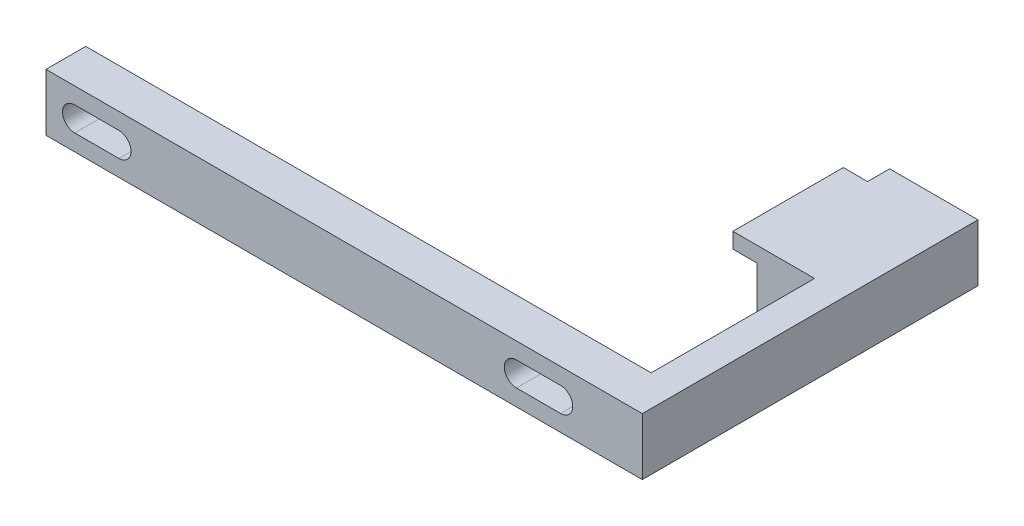
SolidWorks part; units mm, degrees
ref_plane "Front Plane" through (0, 0, 0) normal (0, 0, 1) x (1, 0, 0)
ref_plane "Top Plane" through (0, 0, 0) normal (0, 1, 0) x (1, 0, 0)
ref_plane "Right Plane" through (0, 0, 0) normal (1, 0, 0) x (0, 0, -1)
sketch "Sketch1" plane through (0, 0, 0) normal (0, 0, 1) x (1, 0, 0)
  line L1 (-7.5, -6.4688) -> (127.5, -6.4688)
  line L2 (-7.5, -6.4688) -> (-7.5, 6.4688)
  line L3 (-7.5, 6.4688) -> (127.5, 6.4688)
  line L4 (127.5, -6.4688) -> (127.5, 6.4688)
  point P9 (-7.5, 0)
  dimension "D1" = 12.9376
  dimension "D4" = 135
extrude "Boss-Extrude1" add sketch "Sketch1" along normal blind 9
sketch "Sketch2" plane through (0, 0, 0) normal (0, 0, -1) x (-1, 0, 0)
  line L0 (7.5, -6.4688) -> (-127.5, -6.4688) construction
  line L1 (-127.5, 6.4688) -> (-120.5, 6.4688)
  line L2 (-127.5, 6.4688) -> (-127.5, -6.4688)
  line L3 (-127.5, -6.4688) -> (-120.5, -6.4688)
  line L4 (-120.5, 6.4688) -> (-120.5, -6.4688)
  dimension "D1" = 7
extrude "Boss-Extrude2" add sketch "Sketch2" along direction (0, 0, -1) on the side of the normal offset from surface (54 mm away) 63
sketch "Sketch3" plane through (120.5, 0, 0) normal (-1, 0, 0) x (0, 0, 1)
  line L0 (-54, -6.4688) -> (0, -6.4688) construction
  line L1 (-54, 6.4688) -> (-47, 6.4688)
  line L2 (-54, 6.4688) -> (-54, -6.4688)
  line L3 (-54, -6.4688) -> (-47, -6.4688)
  line L4 (-47, 6.4688) -> (-47, -6.4688)
  dimension "D1" = 7
ref_plane "Plane2" through (97.5, 0, 0) normal (1, 0, 0) x (0, 0, -1)
extrude "Boss-Extrude5" add sketch "Sketch3" along direction (1, 0, 0) on the side of the normal offset from surface (13 mm away) 10 up to plane "Plane2"
sketch "Sketch6" plane through (107.5, 0, 0) normal (-1, 0, 0) x (0, 0, 1)
  line L0 (-37, 6.4688) -> (-37, -6.4688)
  line L1 (-47, 6.4688) -> (0, 6.4688) construction
  line L2 (-47, -6.4688) -> (0, -6.4688) construction
  line L3 (-37, -6.4688) -> (-67, -6.4688)
  line L4 (-67, -6.4688) -> (-67, 6.4688)
  line L5 (-67, 6.4688) -> (-37, 6.4688)
  line L6 (-47, -6.4688) -> (-47, 6.4688) construction
  dimension "D1" = 10
  dimension "D2" = 30
extrude "Boss-Extrude6" add sketch "Sketch6" against normal up to surface (20 mm away) up to face at (127.5, 0, -22.5)
sketch "Sketch7" plane through (107.5, 0, 0) normal (-1, 0, 0) x (0, 0, 1)
  line L3 (-37, -6.4688) -> (-37, 6.4688) construction
  line L5 (-37, -6.4688) -> (-67, -6.4688) construction
  circle A0 centre (-39.75, -3.7188) radius 1.5
  circle A1 centre (-58.8, -3.7188) radius 1.5
  dimension "D2" = 3
  dimension "D3" = 1.25
  dimension "D4" = 1.25
  dimension "D1" = 19.05
extrude "Cut-Extrude1" cut sketch "Sketch7" against normal blind 5
sketch "Sketch9" plane through (107.5, 0, 0) normal (-1, 0, 0) x (0, 0, 1)
  line L0 (-37, -6.4688) -> (-37, 6.4688) construction
  line L1 (-62, 6.4688) -> (-37, 6.4688)
  line L2 (-62, 6.4688) -> (-62, 2.9688)
  line L3 (-62, 2.9688) -> (-37, 2.9688)
  line L4 (-37, 6.4688) -> (-37, 2.9688)
  dimension "D1" = 3.5
  dimension "D2" = 25
extrude "Boss-Extrude7" add sketch "Sketch9" along normal blind 5.5
sketch "Sketch12" plane through (0, 0, 9) normal (0, 0, 1) x (1, 0, 0)
  line L0 (-1, 0) -> (9, 0) construction
  line L1 (-1, 2.75) -> (9, 2.75)
  line L2 (-1, -2.75) -> (9, -2.75)
  line L3 (109, 0) -> (99, 0) construction
  line L4 (109, -2.75) -> (99, -2.75)
  line L5 (109, 2.75) -> (99, 2.75)
  line L6 (-7.5, 6.4688) -> (-7.5, -6.4688) construction
  arc A0 (-1, 2.75) -> (-1, -2.75) centre (-1, 0) ccw
  arc A1 (9, -2.75) -> (9, 2.75) centre (9, 0) ccw
  arc A2 (109, -2.75) -> (109, 2.75) centre (109, 0) ccw
  arc A3 (99, 2.75) -> (99, -2.75) centre (99, 0) ccw
  point P3 (4, 0)
  point P8 (104, 0)
  dimension "D3" = 2.75
  dimension "D1" = 6.5
  dimension "D2" = 10
  dimension "D4" = 10
  dimension "D5" = 100
extrude "Cut-Extrude3" cut sketch "Sketch12" against normal up to surface (9 mm away) up to face at (56.5, 0, 0)
